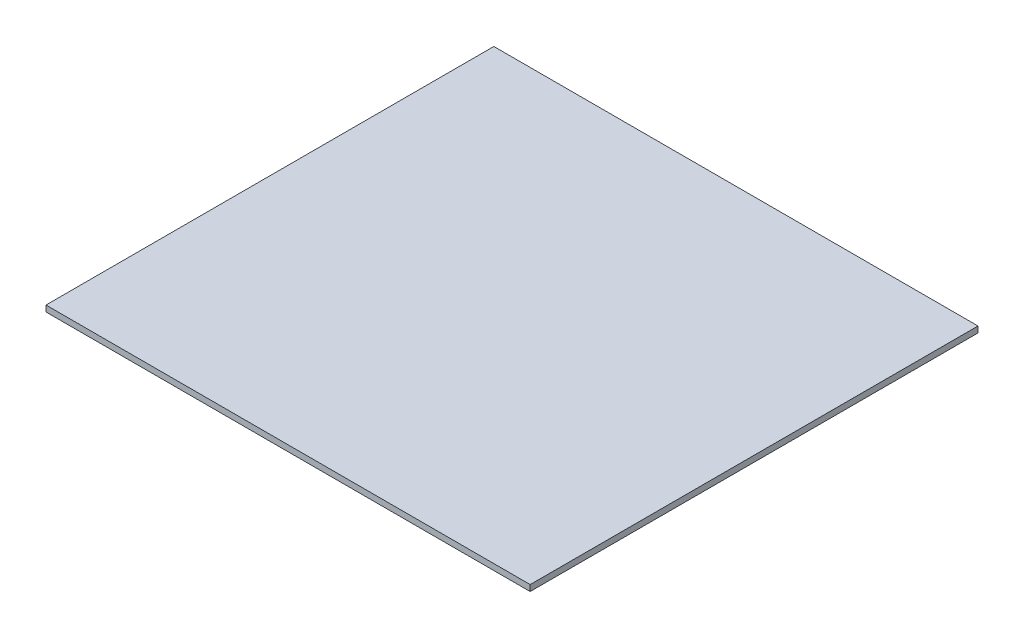
SolidWorks part; units mm, degrees
ref_plane "Front Plane" through (0, 0, 0) normal (0, 0, 1) x (1, 0, 0)
ref_plane "Top Plane" through (0, 0, 0) normal (0, 1, 0) x (1, 0, 0)
ref_plane "Right Plane" through (0, 0, 0) normal (1, 0, 0) x (0, 0, -1)
sketch "Sketch1" plane through (0, 0, 0) normal (0, 1, 0) x (1, 0, 0)
  line L1 (0, 0) -> (508, 0)
  line L2 (0, 0) -> (0, 469.9)
  line L3 (0, 469.9) -> (508, 469.9)
  line L4 (508, 0) -> (508, 469.9)
  dimension "D1" = 508
  dimension "D2" = 469.9
extrude "Boss-Extrude1" add sketch "Sketch1" along normal blind 6.35
ref_plane "Plane1" through (0, 0, -234.95) normal (0, 0, -1) x (-1, 0, 0)
ref_plane "Plane2" through (254, 0, 0) normal (1, 0, 0) x (0, 0, -1)
